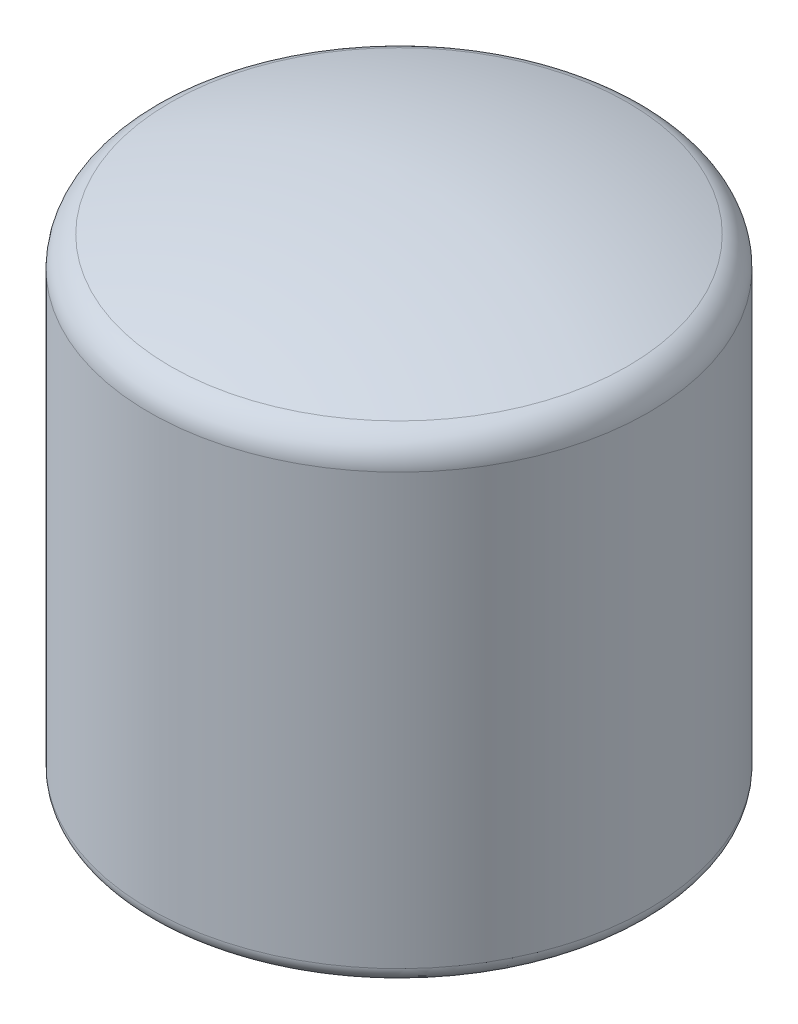
SolidWorks part; units mm, degrees
ref_plane "Plan de face" through (0, 0, 0) normal (0, 0, 1) x (1, 0, 0)
ref_plane "Plan de dessus" through (0, 0, 0) normal (0, 1, 0) x (1, 0, 0)
ref_plane "Plan de droite" through (0, 0, 0) normal (1, 0, 0) x (0, 0, -1)
sketch "Esquisse1" plane through (0, 0, 0) normal (0, 0, 1) x (1, 0, 0)
  line L0 (0, 0) -> (0, 31.9) construction
  line L1 (-12.5, 3.8574) -> (-12.5, 6.3) construction
  line L2 (-16, 0) -> (-16, 31.9) construction
  line L3 (-16, 31.9) -> (0, 31.9) construction
  line L4 (0, 31.9) -> (0, 28.9)
  line L5 (0, 28.9) -> (-11.5, 28.9) construction
  line L21 (-12.5, 28.9) -> (0, 28.9)
  line L22 (-12.5, 6.3) -> (-12.5, 3)
  line L23 (-12.5, 3) -> (-9, 3)
  line L24 (-9, 3) -> (-9, 0)
  line L25 (-9, 0) -> (-12.5, 0)
  line L26 (-16, 0) -> (-12.5, 0)
  line L27 (-12.5, 6.3) -> (-9, 6.3)
  line L28 (-9, 6.3) -> (-9, 9.3)
  line L29 (-9, 9.3) -> (-12.5, 9.3)
  line L30 (-12.5, 9.3) -> (-12.5, 12.6)
  line L31 (-12.5, 12.6) -> (-12.5, 28.9)
  line L32 (-16, 0) -> (-16, 29.9595)
  line L33 (0, 32.9) -> (-6.6204, 32.9) construction
  line L34 (0, 31.9) -> (0, 32.9) construction
  line L35 (0, 32.9) -> (0, 31.9)
  arc A0 (-16, 29.9595) -> (0, 32.9) centre (0, -12.1) cw
  point P15 (-12.5, 20.75)
  dimension "D12" = 45
  dimension "D1" = 3.5
  dimension "D2" = 3.3
  dimension "D3" = 9
  dimension "D4" = 3
  dimension "D5" = 3.5
  dimension "D6" = 16.3
  dimension "D7" = 16
  dimension "D8" = 28.9
  dimension "D9" = 3
  dimension "D10" = 90
  dimension "D11" = 1
revolve "Révolution1" add sketch "Esquisse1" angle 360 about L0
fillet "Congé1" radius 2 1 edges at (16, 29.9595, 0)
fillet "Congé2" radius 1 1 edges at (16, 0, 0)
